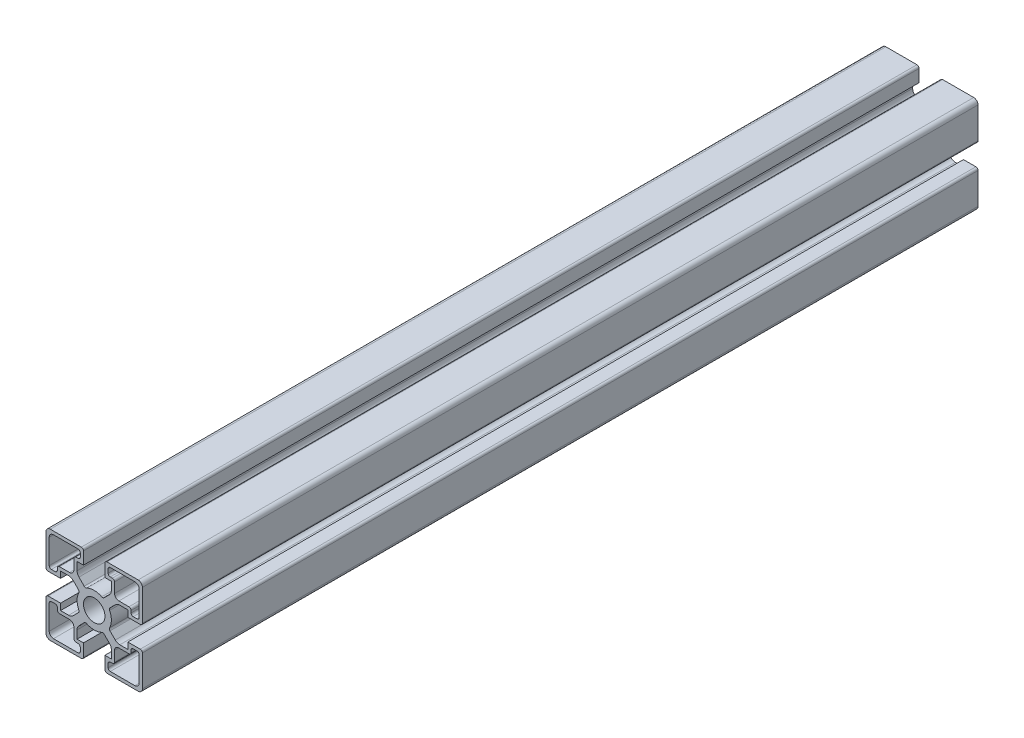
SolidWorks part; units mm, degrees
ref_plane "Front Plane" through (0, 0, 0) normal (0, 0, 1) x (1, 0, 0)
ref_plane "Top Plane" through (0, 0, 0) normal (0, 1, 0) x (1, 0, 0)
ref_plane "Right Plane" through (0, 0, 0) normal (1, 0, 0) x (0, 0, -1)
sketch "Sketch1" plane through (0, 0, 0) normal (0, 0, 1) x (1, 0, 0)
  line L0 (-5, -15.7059) -> (-8, -15.7059)
  line L1 (-20.5, -22.5) -> (-6, -22.5)
  line L2 (-22.5, -20.5) -> (-22.5, -6)
  line L5 (-21.9142, -21.9142) -> (22.5, 22.5) construction
  line L6 (-22.5, 22.5) -> (22.5, -22.5) construction
  line L7 (-20.5, -22.5) -> (-6, -22.5)
  line L8 (-22.5, -20.5) -> (-22.5, -6)
  line L10 (-5, -21.5) -> (-5, -15.7059)
  line L11 (-8, -15.7059) -> (-8, -11.9485)
  line L12 (-7.1213, -9.8272) -> (-4.6684, -7.3742)
  line L14 (-19, -21) -> (-7.5, -21)
  line L15 (-6.5, -20) -> (-6.5, -18.2059)
  line L16 (-7.5, -17.2059) -> (-8.5, -17.2059)
  line L17 (-9.5, -16.2059) -> (-9.5, -11.5)
  line L18 (-16.2059, -9.5) -> (-11.5, -9.5)
  line L19 (-17.2059, -7.5) -> (-17.2059, -8.5)
  line L20 (-20, -6.5) -> (-18.2059, -6.5)
  line L21 (-21, -19) -> (-21, -7.5)
  line L22 (-9.8272, -7.1213) -> (-7.3742, -4.6684)
  line L23 (-15.7059, -8) -> (-11.9485, -8)
  line L24 (-15.7059, -5) -> (-15.7059, -8)
  line L25 (-21.5, -5) -> (-15.7059, -5)
  line L26 (0, 27.7778) -> (0, -29.5537) construction
  line L27 (-31.2741, 0) -> (30.8136, 0) construction
  line L28 (-9.5, 16.2059) -> (-9.5, 11.5)
  line L29 (-16.2059, 9.5) -> (-11.5, 9.5)
  line L30 (-17.2059, 7.5) -> (-17.2059, 8.5)
  line L31 (-20, 6.5) -> (-18.2059, 6.5)
  line L32 (-21, 19) -> (-21, 7.5)
  line L33 (-19, 21) -> (-7.5, 21)
  line L34 (-6.5, 20) -> (-6.5, 18.2059)
  line L35 (-7.5, 17.2059) -> (-8.5, 17.2059)
  line L36 (-22.5, 20.5) -> (-22.5, 6)
  line L37 (-20.5, 22.5) -> (-6, 22.5)
  line L38 (-5, 21.5) -> (-5, 15.7059)
  line L39 (-5, 15.7059) -> (-8, 15.7059)
  line L40 (-8, 15.7059) -> (-8, 11.9485)
  line L41 (-7.1213, 9.8272) -> (-4.6684, 7.3742)
  line L42 (-9.8272, 7.1213) -> (-7.3742, 4.6684)
  line L43 (-15.7059, 8) -> (-11.9485, 8)
  line L44 (-15.7059, 5) -> (-15.7059, 8)
  line L45 (-21.5, 5) -> (-15.7059, 5)
  line L46 (16.2059, 9.5) -> (11.5, 9.5)
  line L47 (9.5, 16.2059) -> (9.5, 11.5)
  line L48 (7.5, 17.2059) -> (8.5, 17.2059)
  line L49 (6.5, 20) -> (6.5, 18.2059)
  line L50 (19, 21) -> (7.5, 21)
  line L51 (21, 19) -> (21, 7.5)
  line L52 (20, 6.5) -> (18.2059, 6.5)
  line L53 (17.2059, 7.5) -> (17.2059, 8.5)
  line L54 (20.5, 22.5) -> (6, 22.5)
  line L55 (22.5, 20.5) -> (22.5, 6)
  line L56 (21.5, 5) -> (15.7059, 5)
  line L57 (15.7059, 5) -> (15.7059, 8)
  line L58 (15.7059, 8) -> (11.9485, 8)
  line L59 (9.8272, 7.1213) -> (7.3742, 4.6684)
  line L60 (7.1213, 9.8272) -> (4.6684, 7.3742)
  line L61 (8, 15.7059) -> (8, 11.9485)
  line L62 (5, 15.7059) -> (8, 15.7059)
  line L63 (5, 21.5) -> (5, 15.7059)
  line L64 (9.5, -16.2059) -> (9.5, -11.5)
  line L65 (16.2059, -9.5) -> (11.5, -9.5)
  line L66 (17.2059, -7.5) -> (17.2059, -8.5)
  line L67 (20, -6.5) -> (18.2059, -6.5)
  line L68 (21, -19) -> (21, -7.5)
  line L69 (19, -21) -> (7.5, -21)
  line L70 (6.5, -20) -> (6.5, -18.2059)
  line L71 (7.5, -17.2059) -> (8.5, -17.2059)
  line L72 (22.5, -20.5) -> (22.5, -6)
  line L73 (20.5, -22.5) -> (6, -22.5)
  line L74 (5, -21.5) -> (5, -15.7059)
  line L75 (5, -15.7059) -> (8, -15.7059)
  line L76 (8, -15.7059) -> (8, -11.9485)
  line L77 (7.1213, -9.8272) -> (4.6684, -7.3742)
  line L78 (9.8272, -7.1213) -> (7.3742, -4.6684)
  line L79 (15.7059, -8) -> (11.9485, -8)
  line L80 (15.7059, -5) -> (15.7059, -8)
  line L81 (21.5, -5) -> (15.7059, -5)
  circle A0 centre (0, 0) radius 5
  arc A1 (-3.5211, -7.1834) -> (3.5211, -7.1834) centre (0, 0) ccw
  arc A2 (-3.5211, -7.1834) -> (-4.6684, -7.3742) centre (-3.9613, -8.0814) ccw
  arc A3 (-8, -11.9485) -> (-7.1213, -9.8272) centre (-5, -11.9485) cw
  arc A4 (-6, -22.5) -> (-5, -21.5) centre (-6, -21.5) ccw
  arc A5 (-8.5, -17.2059) -> (-9.5, -16.2059) centre (-8.5, -16.2059) cw
  arc A6 (-6.5, -18.2059) -> (-7.5, -17.2059) centre (-7.5, -18.2059) ccw
  arc A7 (-6.5, -20) -> (-7.5, -21) centre (-7.5, -20) cw
  arc A8 (-17.2059, -8.5) -> (-16.2059, -9.5) centre (-16.2059, -8.5) ccw
  arc A9 (-18.2059, -6.5) -> (-17.2059, -7.5) centre (-18.2059, -7.5) cw
  arc A10 (-20, -6.5) -> (-21, -7.5) centre (-20, -7.5) ccw
  arc A11 (-22.5, -20.5) -> (-20.5, -22.5) centre (-20.5, -20.5) ccw
  arc A12 (-9.5, -11.5) -> (-11.5, -9.5) centre (-11.5, -11.5) ccw
  arc A13 (-19, -21) -> (-21, -19) centre (-19, -19) cw
  arc A14 (-7.1834, -3.5211) -> (-7.3742, -4.6684) centre (-8.0814, -3.9613) cw
  arc A15 (-11.9485, -8) -> (-9.8272, -7.1213) centre (-11.9485, -5) ccw
  arc A16 (-22.5, -6) -> (-21.5, -5) centre (-21.5, -6) cw
  arc A17 (-11.5, 9.5) -> (-9.5, 11.5) centre (-11.5, 11.5) ccw
  arc A18 (-17.2059, 8.5) -> (-16.2059, 9.5) centre (-16.2059, 8.5) cw
  arc A19 (-18.2059, 6.5) -> (-17.2059, 7.5) centre (-18.2059, 7.5) ccw
  arc A20 (-20, 6.5) -> (-21, 7.5) centre (-20, 7.5) cw
  arc A21 (-21, 19) -> (-19, 21) centre (-19, 19) cw
  arc A22 (-6.5, 20) -> (-7.5, 21) centre (-7.5, 20) ccw
  arc A23 (-6.5, 18.2059) -> (-7.5, 17.2059) centre (-7.5, 18.2059) cw
  arc A24 (-8.5, 17.2059) -> (-9.5, 16.2059) centre (-8.5, 16.2059) ccw
  arc A25 (-20.5, 22.5) -> (-22.5, 20.5) centre (-20.5, 20.5) ccw
  arc A26 (-6, 22.5) -> (-5, 21.5) centre (-6, 21.5) cw
  arc A27 (-8, 11.9485) -> (-7.1213, 9.8272) centre (-5, 11.9485) ccw
  arc A28 (-3.5211, 7.1834) -> (-4.6684, 7.3742) centre (-3.9613, 8.0814) cw
  arc A29 (-7.1834, 3.5211) -> (-7.3742, 4.6684) centre (-8.0814, 3.9613) ccw
  arc A30 (-11.9485, 8) -> (-9.8272, 7.1213) centre (-11.9485, 5) cw
  arc A31 (-22.5, 6) -> (-21.5, 5) centre (-21.5, 6) ccw
  arc A32 (9.5, 11.5) -> (11.5, 9.5) centre (11.5, 11.5) ccw
  arc A33 (8.5, 17.2059) -> (9.5, 16.2059) centre (8.5, 16.2059) cw
  arc A34 (6.5, 18.2059) -> (7.5, 17.2059) centre (7.5, 18.2059) ccw
  arc A35 (6.5, 20) -> (7.5, 21) centre (7.5, 20) cw
  arc A36 (19, 21) -> (21, 19) centre (19, 19) cw
  arc A37 (20, 6.5) -> (21, 7.5) centre (20, 7.5) ccw
  arc A38 (18.2059, 6.5) -> (17.2059, 7.5) centre (18.2059, 7.5) cw
  arc A39 (17.2059, 8.5) -> (16.2059, 9.5) centre (16.2059, 8.5) ccw
  arc A40 (22.5, 20.5) -> (20.5, 22.5) centre (20.5, 20.5) ccw
  arc A41 (22.5, 6) -> (21.5, 5) centre (21.5, 6) cw
  arc A42 (11.9485, 8) -> (9.8272, 7.1213) centre (11.9485, 5) ccw
  arc A43 (7.1834, 3.5211) -> (7.3742, 4.6684) centre (8.0814, 3.9613) cw
  arc A44 (3.5211, 7.1834) -> (4.6684, 7.3742) centre (3.9613, 8.0814) ccw
  arc A45 (8, 11.9485) -> (7.1213, 9.8272) centre (5, 11.9485) cw
  arc A46 (6, 22.5) -> (5, 21.5) centre (6, 21.5) ccw
  arc A47 (11.5, -9.5) -> (9.5, -11.5) centre (11.5, -11.5) ccw
  arc A48 (17.2059, -8.5) -> (16.2059, -9.5) centre (16.2059, -8.5) cw
  arc A49 (18.2059, -6.5) -> (17.2059, -7.5) centre (18.2059, -7.5) ccw
  arc A50 (20, -6.5) -> (21, -7.5) centre (20, -7.5) cw
  arc A51 (21, -19) -> (19, -21) centre (19, -19) cw
  arc A52 (6.5, -20) -> (7.5, -21) centre (7.5, -20) ccw
  arc A53 (6.5, -18.2059) -> (7.5, -17.2059) centre (7.5, -18.2059) cw
  arc A54 (8.5, -17.2059) -> (9.5, -16.2059) centre (8.5, -16.2059) ccw
  arc A55 (20.5, -22.5) -> (22.5, -20.5) centre (20.5, -20.5) ccw
  arc A56 (6, -22.5) -> (5, -21.5) centre (6, -21.5) cw
  arc A57 (8, -11.9485) -> (7.1213, -9.8272) centre (5, -11.9485) ccw
  arc A58 (3.5211, -7.1834) -> (4.6684, -7.3742) centre (3.9613, -8.0814) cw
  arc A59 (7.1834, -3.5211) -> (7.3742, -4.6684) centre (8.0814, -3.9613) ccw
  arc A60 (11.9485, -8) -> (9.8272, -7.1213) centre (11.9485, -5) cw
  arc A61 (22.5, -6) -> (21.5, -5) centre (21.5, -6) ccw
  arc A62 (-7.1834, 3.5211) -> (-7.1834, -3.5211) centre (0, 0) ccw
  arc A63 (3.5211, 7.1834) -> (-3.5211, 7.1834) centre (0, 0) ccw
  arc A64 (7.1834, -3.5211) -> (7.1834, 3.5211) centre (0, 0) ccw
  point P0 (0, 0)
  point P19 (-8, -10.7059)
  point P48 (-9.5, -9.5)
  point P51 (-21, -21)
  point P214 (0, 0)
  dimension "D3" = 17.5
  dimension "D5" = 1
  dimension "D6" = 3
  dimension "D2" = 1
  dimension "D11" = 1
  dimension "D12" = 2
  dimension "D1" = 45
  dimension "D4" = 5
  dimension "D7" = 1.5
  dimension "D8" = 1.5
  dimension "D9" = 1.5
  dimension "D10" = 1.5
  dimension "D13" = 4
extrude "Boss-Extrude1" add sketch "Sketch1" along normal blind 390 contours A59 A64 A43 L59 A42 L58 L57 L56 A41 L55 A40 L54 A46 L63 L62 L61 A45 L60 A44 A63 A28 L41 A27 L40 L39 L38 A26 L37 A25 L36 A31 L45 L44 L43 A30 L42 A29 A62 A14 L22 A15 L23 L24 L25 A16 L2 A11 L1 A4 L10 L0
